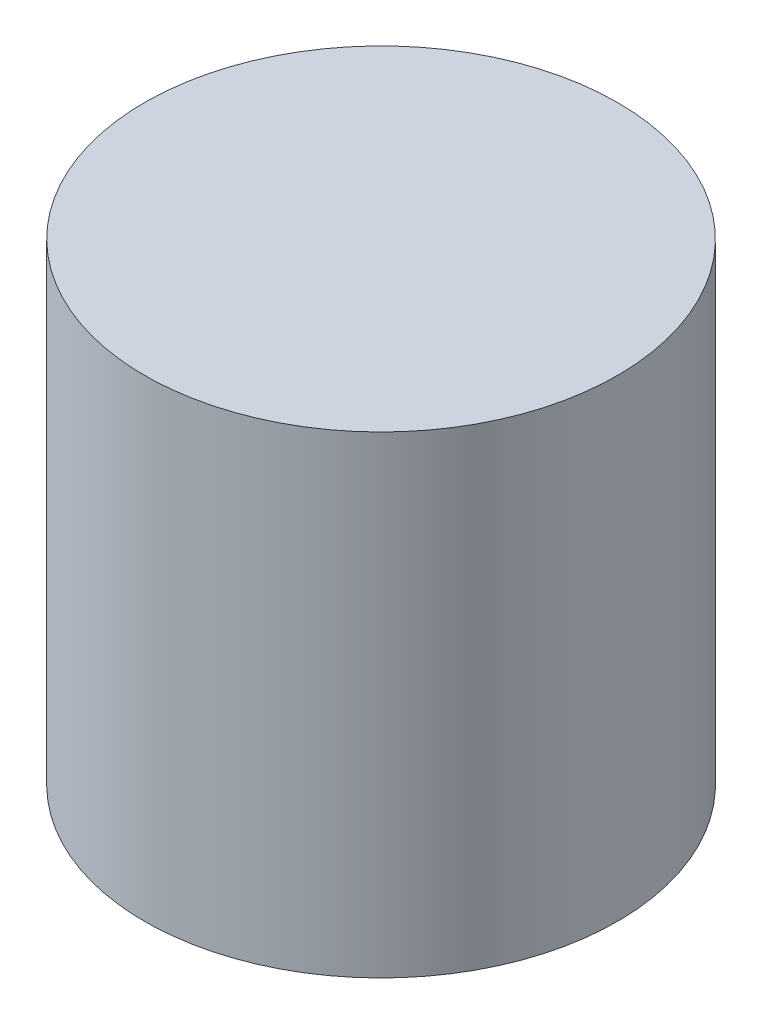
SolidWorks part; units mm, degrees
ref_plane "Front Plane" through (0, 0, 0) normal (0, 0, 1) x (1, 0, 0)
ref_plane "Top Plane" through (0, 0, 0) normal (0, 1, 0) x (1, 0, 0)
ref_plane "Right Plane" through (0, 0, 0) normal (1, 0, 0) x (0, 0, -1)
sketch "Sketch1" plane through (0, 0, 0) normal (0, 1, 0) x (1, 0, 0)
  circle A0 centre (0, 0) radius 38.1
  dimension "D1" = 76.2
extrude "Boss-Extrude1" add sketch "Sketch1" along normal blind 76.2
